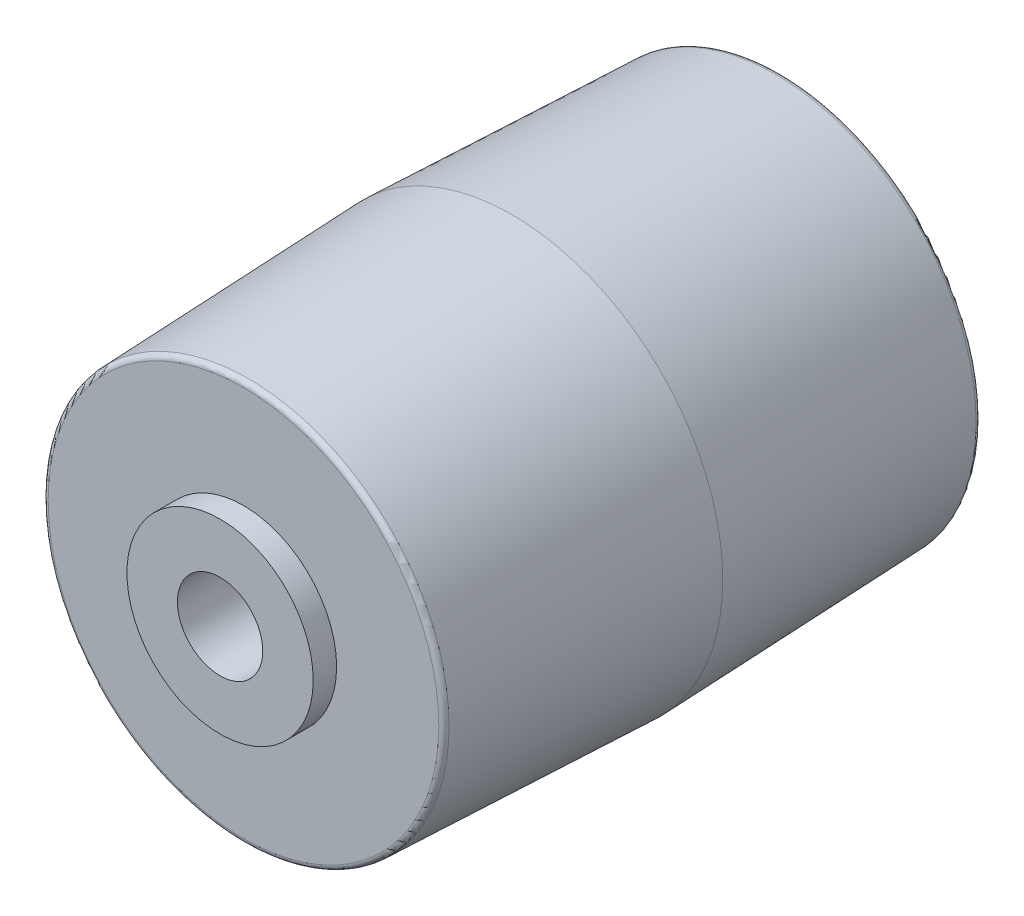
SolidWorks part; units mm, degrees
ref_plane "Front Plane" through (0, 0, 0) normal (0, 0, 1) x (1, 0, 0)
ref_plane "Top Plane" through (0, 0, 0) normal (0, 1, 0) x (1, 0, 0)
ref_plane "Right Plane" through (0, 0, 0) normal (1, 0, 0) x (0, 0, -1)
sketch "Sketch1" plane through (0, 0, 0) normal (1, 0, 0) x (0, 0, -1)
  line L0 (-7.1247, 0) -> (-7.1247, 2.2733)
  line L1 (-7.1247, 2.2733) -> (-6.5532, 2.2733)
  line L2 (-6.5532, 2.2733) -> (-6.5532, 4.8895)
  line L3 (-6.5532, 4.8895) -> (0, 5.1435)
  line L4 (0, 0) -> (0, 5.1435) construction
  line L5 (7.1247, 0) -> (-7.1247, 0) construction
  line L6 (6.5532, 4.8895) -> (0, 5.1435)
  line L7 (6.5532, 2.2733) -> (6.5532, 4.8895)
  line L8 (7.1247, 2.2733) -> (6.5532, 2.2733)
  line L9 (7.1247, 0) -> (7.1247, 2.2733)
  line L10 (-7.1247, 0) -> (7.1247, 0)
  dimension "D1" = 14.2494
  dimension "D2" = 13.1064
  dimension "D3" = 10.287
  dimension "D4" = 9.779
  dimension "D5" = 4.5466
revolve "Revolve1" add sketch "Sketch1" angle 360 about L10
sketch "Sketch2" plane through (0, 0, 7.1247) normal (0, 0, 1) x (1, 0, 0)
  circle A0 centre (0, 0) radius 1.0414
  dimension "D1" = 2.0828
extrude "Cut-Extrude1" cut sketch "Sketch2" against normal through all
fillet "Fillet1" radius 0.127 2 edges at (4.8895, 0, 6.5532) (4.8895, 0, -6.5532)
